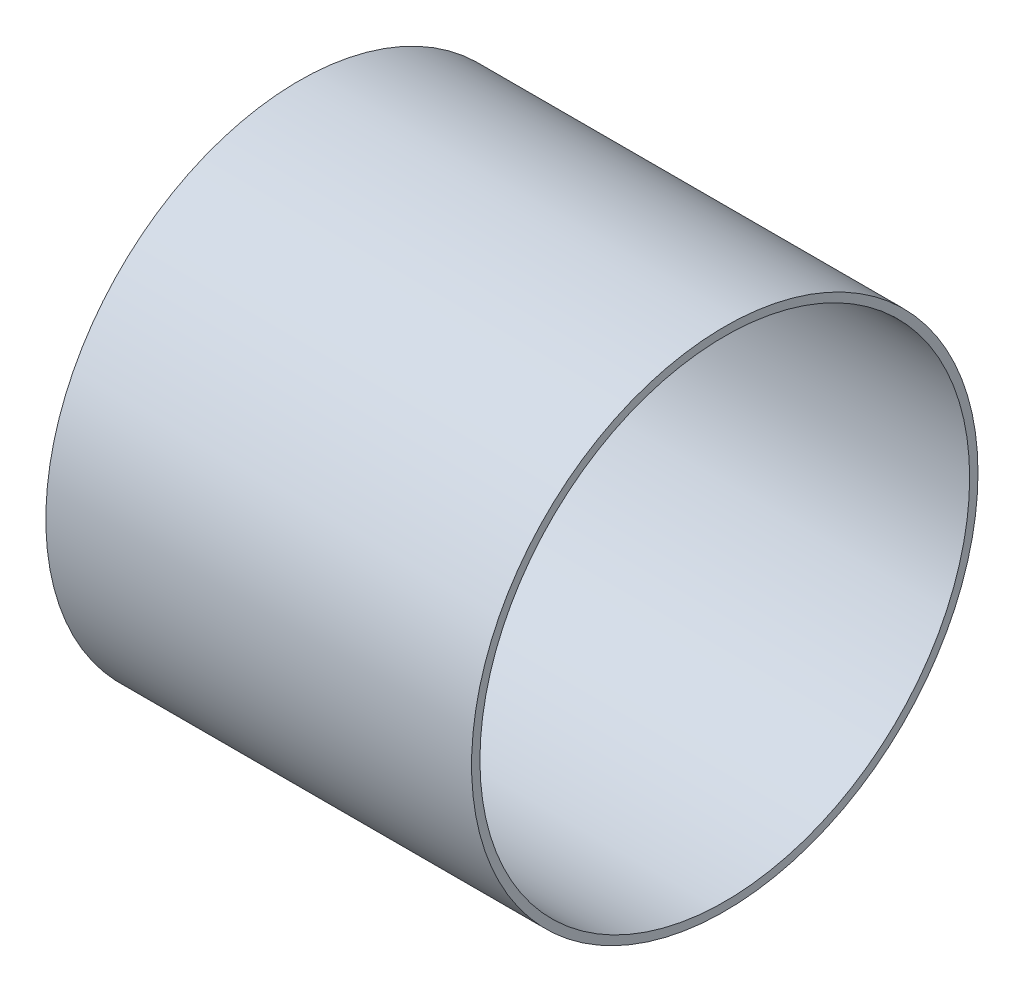
SolidWorks part; units mm, degrees
material "Thornel Mat VMA"
ref_plane "Front Plane" through (0, 0, 0) normal (0, 0, 1) x (1, 0, 0)
ref_plane "Top Plane" through (0, 0, 0) normal (0, 1, 0) x (1, 0, 0)
ref_plane "Right Plane" through (0, 0, 0) normal (1, 0, 0) x (0, 0, -1)
sketch "Sketch1" plane through (0, 0, 0) normal (1, 0, 0) x (0, 0, -1)
  circle A0 centre (0, 0) radius 44
  circle A1 centre (0, 0) radius 45.5
  dimension "D1" = 91
  dimension "D2" = 88
extrude "Boss-Extrude1" add sketch "Sketch1" along normal mid plane 76.5
